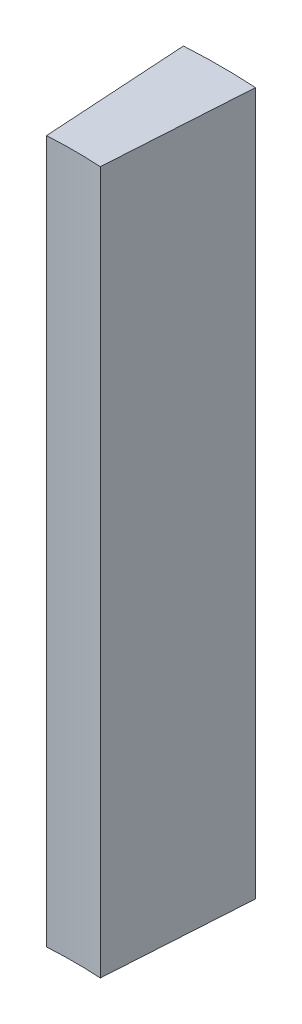
SolidWorks part; units mm, degrees
material "PTFE (general)"
ref_plane "Front Plane" through (0, 0, 0) normal (0, 0, 1) x (1, 0, 0)
ref_plane "Top Plane" through (0, 0, 0) normal (0, 1, 0) x (1, 0, 0)
ref_plane "Right Plane" through (0, 0, 0) normal (1, 0, 0) x (0, 0, -1)
sketch "Sketch1" plane through (0, 0, 0) normal (0, 1, 0) x (1, 0, -0.0097)
  line L0 (-28.3271, 38.4673) -> (-29.0476, 28.4932)
  line L1 (-33.2507, 38.515) -> (-32.7236, 28.5288)
  arc A0 (-29.0476, 28.4932) -> (-32.7236, 28.5288) centre (-31.171, -0.9523) ccw
  arc A1 (-28.3271, 38.4673) -> (-33.2507, 38.515) centre (-31.171, -0.9523) ccw
  dimension "D1" = 29.522
  dimension "D2" = 39.522
extrude "Boss-Extrude1" add sketch "Sketch1" along normal blind 48
sketch "Sketch2" plane through (0, 48, 0) normal (0, 1, 0) x (1, 0, 0)
  line L0 (-31.1603, 38.2678) -> (-31.1603, 23.6711) construction
  arc A0 (-28.6984, 38.191) -> (-33.6222, 38.191) centre (-31.1603, -1.2542) ccw construction
